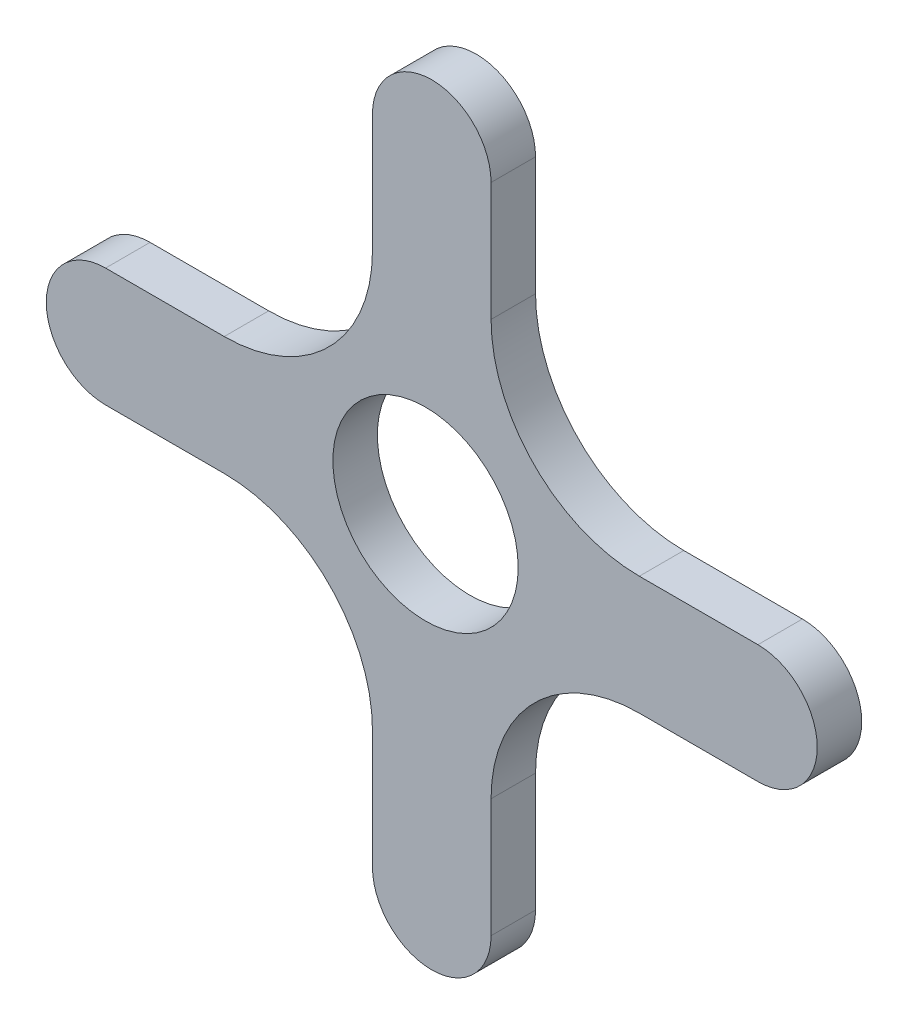
SolidWorks part; units mm, degrees
ref_plane "Front Plane" through (0, 0, 0) normal (0, 0, 1) x (1, 0, 0)
ref_plane "Top Plane" through (0, 0, 0) normal (0, 1, 0) x (1, 0, 0)
ref_plane "Right Plane" through (0, 0, 0) normal (1, 0, 0) x (0, 0, -1)
sketch "Sketch1" plane through (0, 0, 0) normal (0, 0, 1) x (1, 0, 0)
  line L4 (-3.5806, -22.4194) -> (-3.5806, -14.4194)
  line L6 (4.4194, -22.4194) -> (4.4194, -14.4194)
  line L9 (-21.5806, 3.5806) -> (-13.5806, 3.5806)
  line L11 (-21.5806, -4.4194) -> (-13.5806, -4.4194)
  line L15 (-3.5806, 13.5806) -> (-3.5806, 21.5806)
  line L16 (-3.5806, -0.4194) -> (-3.5806, 0.196)
  line L22 (4.4194, 13.5806) -> (4.4194, 21.5806)
  line L23 (14.4194, -4.4194) -> (22.4194, -4.4194)
  line L24 (14.4194, 3.5806) -> (22.4194, 3.5806)
  arc A0 (-13.5806, -4.4194) -> (-3.5806, -14.4194) centre (-13.5806, -14.4194) cw
  arc A1 (4.4194, -14.4194) -> (14.4194, -4.4194) centre (14.4194, -14.4194) cw
  arc A2 (14.4194, 3.5806) -> (4.4194, 13.5806) centre (14.4194, 13.5806) cw
  arc A3 (-3.5806, 13.5806) -> (-13.5806, 3.5806) centre (-13.5806, 13.5806) cw
  arc A4 (-21.5806, 3.5806) -> (-21.5806, -4.4194) centre (-21.5806, -0.4194) ccw
  arc A5 (4.4194, 21.5806) -> (-3.5806, 21.5806) centre (0.4194, 21.5806) ccw
  arc A6 (22.4194, -4.4194) -> (22.4194, 3.5806) centre (22.4194, -0.4194) ccw
  arc A7 (-3.5806, -22.4194) -> (4.4194, -22.4194) centre (0.4194, -22.4194) ccw
  circle A8 centre (0, 0) radius 6.25
  point P0 (0, 0)
  point P4 (0, 0)
  point P8 (0, 0)
  point P13 (0, 0)
  point P22 (4.4194, -4.4194)
  point P28 (-3.5806, 3.5806)
  dimension "D1" = 10
extrude "Boss-Extrude1" add sketch "Sketch1" along normal blind 3 contours L4 A7 L6 A1 L23 A6 L24 A2 L22 A5 L15 A3 L9 A4 L11 A0 A8
